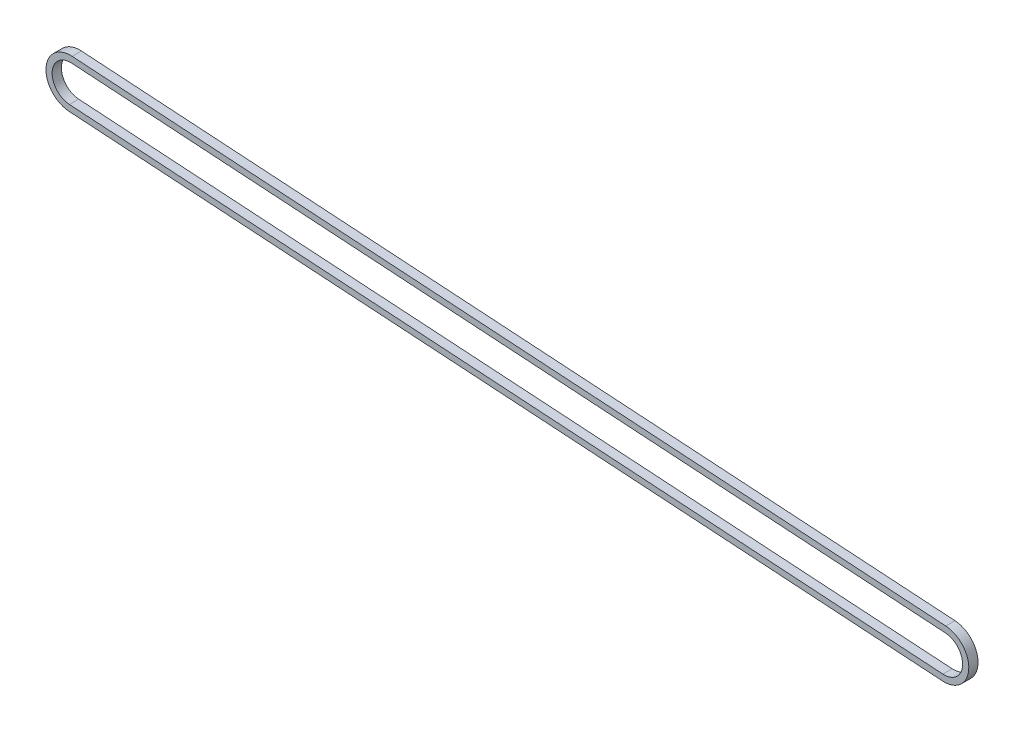
SolidWorks part; units mm, degrees
ref_plane "Front Plane" through (0, 0, 0) normal (0, 0, 1) x (1, 0, 0)
ref_plane "Top Plane" through (0, 0, 0) normal (0, 1, 0) x (1, 0, 0)
ref_plane "Right Plane" through (0, 0, 0) normal (1, 0, 0) x (0, 0, -1)
sketch "Sketch2" plane through (0, 0, 0) normal (0, 0, 1) x (1, 0, 0)
  line L0 (0, 0) -> (1, 0) construction
  line L1 (0, 0) -> (0, 1) construction
  line L2 (0.3878, 5.9875) -> (283.8224, -12.371)
  line L3 (283.0468, -24.3459) -> (-0.3878, -5.9875)
  arc A0 (-0.3878, -5.9875) -> (0.3878, 5.9875) centre (0, 0) cw
  arc A1 (283.8224, -12.371) -> (283.0468, -24.3459) centre (283.4346, -18.3584) cw
extrude "Extrude-Thin1" add sketch "Sketch2" along normal blind 3 thin thin type one direction wall 2
